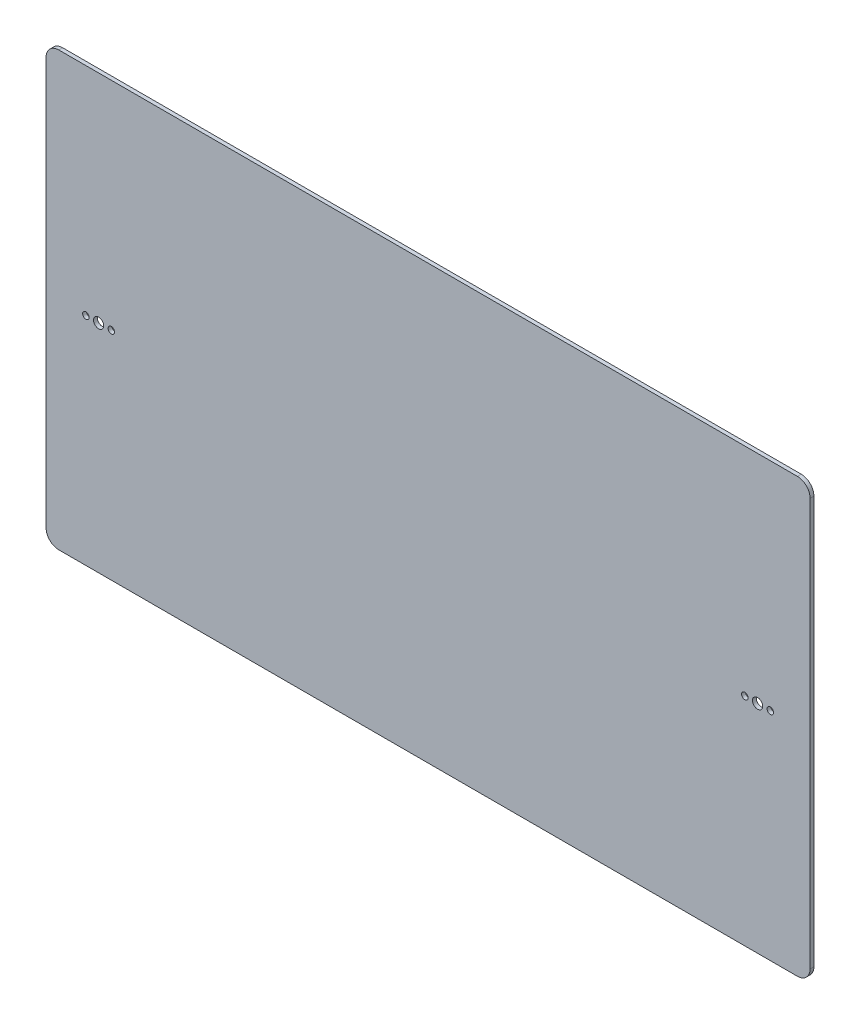
SolidWorks part; units mm, degrees
ref_plane "Alzado" through (0, 0, 0) normal (0, 0, 1) x (1, 0, 0)
ref_plane "Planta" through (0, 0, 0) normal (0, 1, 0) x (1, 0, 0)
ref_plane "Vista lateral" through (0, 0, 0) normal (1, 0, 0) x (0, 0, -1)
sketch "Croquis1" plane through (0, 0, 0) normal (0, 0, 1) x (1, 0, 0)
  line L0 (0, -1000) -> (0, 49000) construction
  line L2 (-290, 170) -> (290, 170)
  line L3 (-300, 160) -> (-300, -160)
  line L4 (-290, -170) -> (290, -170)
  line L5 (300, 160) -> (300, -160)
  line L6 (-300, 170) -> (300, -170) construction
  line L7 (-300, -170) -> (300, 170) construction
  circle A0 centre (258.75, 0) radius 4
  circle A1 centre (248.75, 0) radius 2.55
  circle A2 centre (268.75, 0) radius 2.55
  circle A3 centre (-268.75, 0) radius 2.55
  circle A4 centre (-248.75, 0) radius 2.55
  circle A5 centre (-258.75, 0) radius 4
  arc A6 (290, 170) -> (300, 160) centre (290, 160) cw
  arc A7 (290, -170) -> (300, -160) centre (290, -160) ccw
  arc A8 (-300, -160) -> (-290, -170) centre (-290, -160) ccw
  arc A9 (-290, 170) -> (-300, 160) centre (-290, 160) ccw
  point P9 (0, 0)
  dimension "D1" = 8
  dimension "D3" = 10
  dimension "D4" = 10
  dimension "D5" = 5.1
  dimension "D8" = 10
  dimension "D2" = 258.75
  dimension "D6" = 340
  dimension "D7" = 600
extrude "Saliente-Extruir1" add sketch "Croquis1" along normal blind 3
